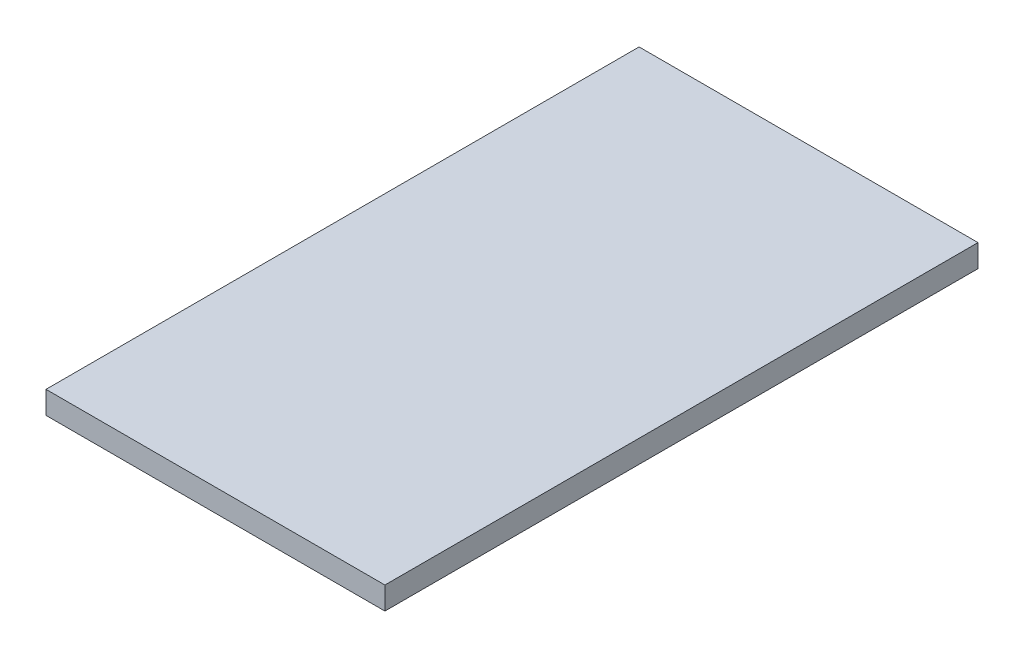
SolidWorks part; units mm, degrees
ref_plane "Front Plane" through (0, 0, 0) normal (0, 0, 1) x (1, 0, 0)
ref_plane "Top Plane" through (0, 0, 0) normal (0, 1, 0) x (1, 0, 0)
ref_plane "Right Plane" through (0, 0, 0) normal (1, 0, 0) x (0, 0, -1)
sketch "Sketch1" plane through (0, 0, 0) normal (0, 1, 0) x (1, 0, 0)
  line L1 (0, 0) -> (24, 0)
  line L2 (0, 0) -> (0, 42)
  line L3 (0, 42) -> (24, 42)
  line L4 (24, 0) -> (24, 42)
  dimension "D1" = 24
  dimension "D2" = 42
extrude "Boss-Extrude1" add sketch "Sketch1" along normal blind 1.6
